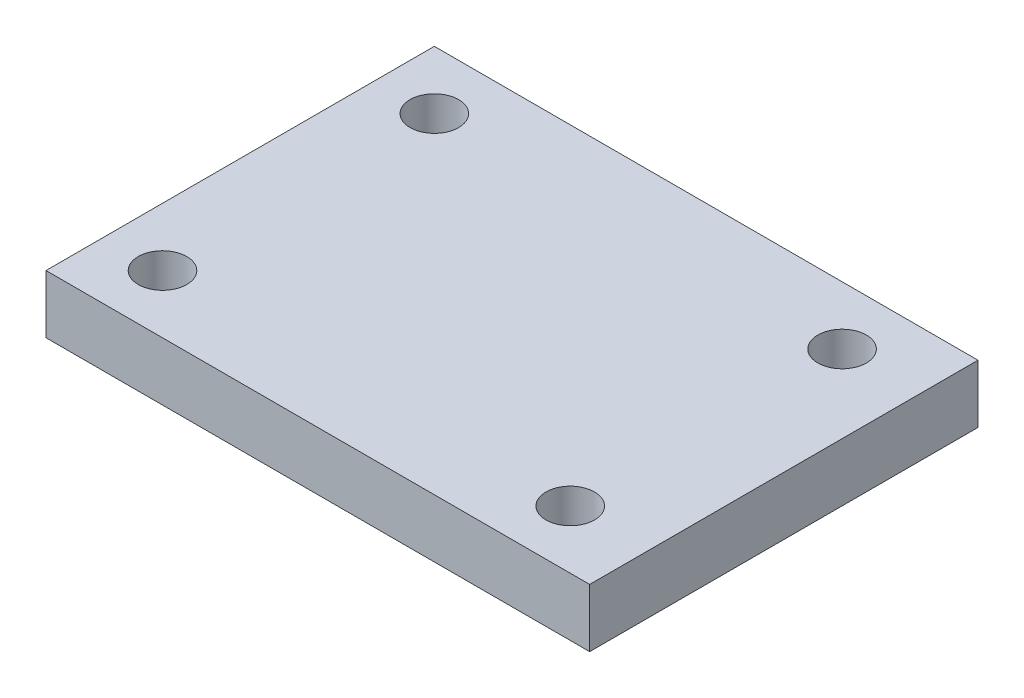
SolidWorks part; units mm, degrees
ref_plane "Front Plane" through (0, 0, 0) normal (0, 0, 1) x (1, 0, 0)
ref_plane "Top Plane" through (0, 0, 0) normal (0, 1, 0) x (1, 0, 0)
ref_plane "Right Plane" through (0, 0, 0) normal (1, 0, 0) x (0, 0, -1)
sketch "Sketch1" plane through (0, 0, 0) normal (0, 1, 0) x (1, 0, 0)
  line L1 (14, -10) -> (-14, -10)
  line L2 (14, -10) -> (14, 10)
  line L3 (14, 10) -> (-14, 10)
  line L4 (-14, -10) -> (-14, 10)
  line L5 (14, -10) -> (-14, 10) construction
  line L6 (14, 10) -> (-14, -10) construction
  point P0 (0, 0)
  dimension "D1" = 20
  dimension "D2" = 28
extrude "Boss-Extrude1" add sketch "Sketch1" along normal blind 3
hole_wizard "M3 Tapped Hole1" positions "Sketch2" profile "Sketch3" tap size "M3" standard "DIN" end condition through all
sketch "Sketch2" plane through (0, 3, 0) normal (0, 1, 0) x (1, 0, 0)
  line L0 (-14, 10) -> (-14, -10) construction
  line L1 (-14, -10) -> (14, -10) construction
  point P0 (-11, 7)
  point P2 (10, 7)
  point P4 (10, -7)
  point P6 (-11, -7)
  point P9 (0, 0)
  point P10 (0, 0)
  point P11 (0, 0)
  point P12 (0, 0)
  dimension "D1" = 3
  dimension "D2" = 14
  dimension "D3" = 3
  dimension "D4" = 21
sketch "Sketch3" plane through (-11, 3, -7) normal (1, 0, 0) x (0, 0, 1)
  line L0 (0, 0) -> (0, 3)
  line L1 (0, 3) -> (1.25, 3)
  line L2 (1.25, 3) -> (1.25, 0)
  line L5 (1.25, 0) -> (0, 0)
  line L11 (0, -6.35) -> (0, 107.95) construction
  dimension "Thru Tap Drill Dia." = 2.5
  dimension "Thru Tap Drill Depth" = 3
cosmetic thread "Hole Thread1"
cosmetic thread "Hole Thread2"
cosmetic thread "Hole Thread3"
cosmetic thread "Hole Thread4"
